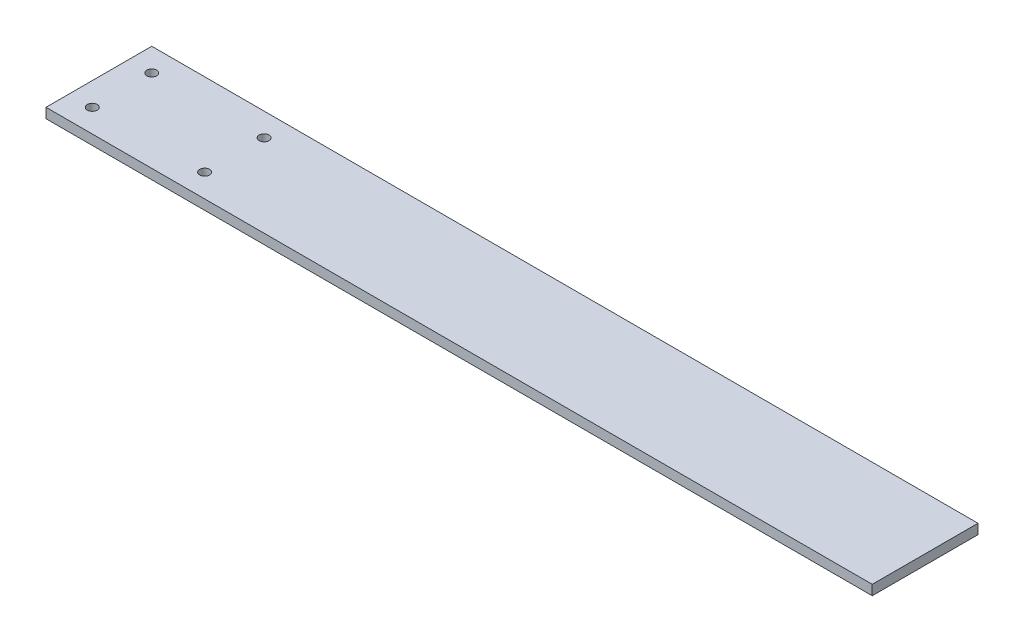
SolidWorks part; units mm, degrees
ref_plane "Front Plane" through (0, 0, 0) normal (0, 0, 1) x (1, 0, 0)
ref_plane "Top Plane" through (0, 0, 0) normal (0, 1, 0) x (1, 0, 0)
ref_plane "Right Plane" through (0, 0, 0) normal (1, 0, 0) x (0, 0, -1)
sketch "Sketch1" plane through (0, 0, 0) normal (0, 1, 0) x (1, 0, 0)
  line L1 (-125, 16) -> (125, 16)
  line L2 (-125, 16) -> (-125, -16)
  line L3 (-125, -16) -> (125, -16)
  line L4 (125, 16) -> (125, -16)
  line L5 (-125, 16) -> (125, -16) construction
  line L6 (-125, -16) -> (125, 16) construction
  circle A0 centre (-118, 9) radius 1.5
  circle A1 centre (-118, -9) radius 1.5
  circle A2 centre (-84, -9) radius 1.5
  circle A3 centre (-84, 9) radius 1.5
  point P0 (0, 0)
  dimension "D3" = 3
  dimension "D4" = 3
  dimension "D5" = 18
  dimension "D6" = 7
  dimension "D7" = 7
  dimension "D8" = 7
  dimension "D9" = 34
  dimension "D10" = 34
  dimension "D11" = 3
  dimension "D12" = 3
  dimension "D13" = 18
  dimension "D14" = 7
  dimension "D1" = 32
  dimension "D2" = 250
extrude "Boss-Extrude1" add sketch "Sketch1" along normal blind 3
